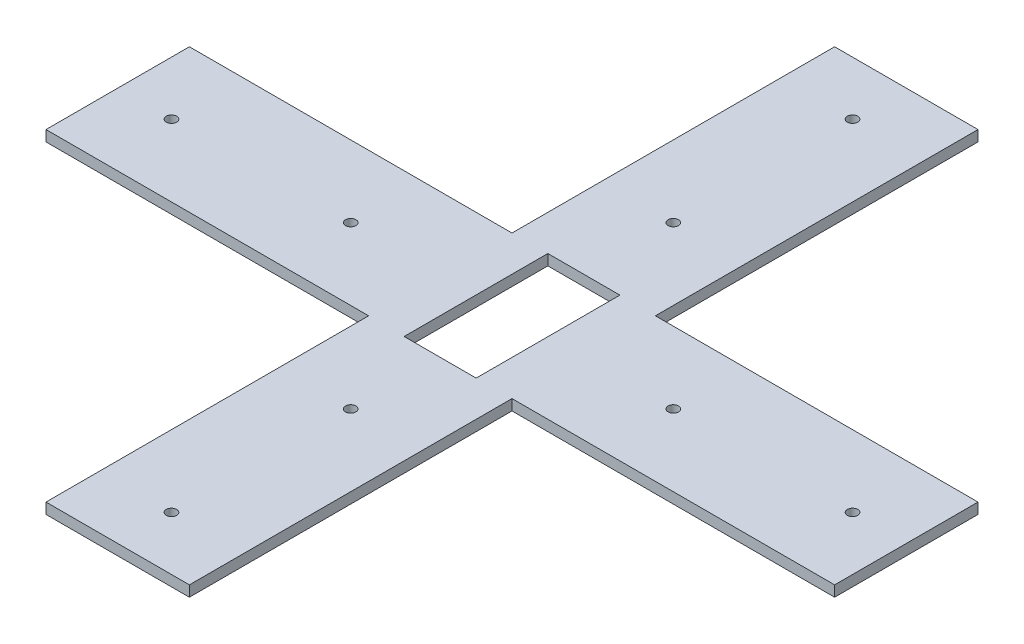
SolidWorks part; units mm, degrees
material "ABS"
ref_plane "Front Plane" through (0, 0, 0) normal (0, 0, 1) x (1, 0, 0)
ref_plane "Top Plane" through (0, 0, 0) normal (0, 1, 0) x (1, 0, 0)
ref_plane "Right Plane" through (0, 0, 0) normal (1, 0, 0) x (0, 0, -1)
sketch "Sketch1" plane through (0, 0, 0) normal (0, 1, 0) x (1, 0, 0)
  line L0 (-10.05, 20) -> (10.05, 20)
  line L1 (-10.05, 20.05) -> (10.05, 20.05)
  line L2 (-10.05, 20.05) -> (-10.05, -20.05)
  line L3 (-10.05, -20.05) -> (10.05, -20.05)
  line L4 (10.05, 20.05) -> (10.05, -20.05)
  line L5 (-10.05, 20.05) -> (10.05, -20.05) construction
  line L6 (-10.05, -20.05) -> (10.05, 20.05) construction
  line L7 (-20, 110) -> (20, 110)
  line L8 (-20, 110) -> (-20, 20)
  line L9 (-20, -110) -> (20, -110)
  line L10 (20, 110) -> (20, 20)
  line L11 (-4.01, 20.05) -> (4.01, -20.05) construction
  line L12 (-4.01, -20.05) -> (4.01, 20.05) construction
  line L13 (-110, 20) -> (-20, 20)
  line L14 (-110, 20) -> (-110, -20)
  line L15 (-110, -20) -> (-20, -20)
  line L16 (110, 20) -> (110, -20)
  line L17 (-10.05, 2.01) -> (10.05, -2.01) construction
  line L18 (-10.05, -2.01) -> (10.05, 2.01) construction
  line L19 (0, 0) -> (0, 16.1139)
  line L20 (-20, -20) -> (-20, -110)
  line L21 (-10.05, -20) -> (10.05, -20)
  line L22 (20, -20) -> (110, -20)
  line L23 (20, -20) -> (20, -110)
  line L24 (0, 0) -> (28.374, 0)
  line L25 (20, 20) -> (110, 20)
  circle A0 centre (45, 0) radius 1.45
  circle A1 centre (95, 0) radius 1.45
  circle A2 centre (-95, 0) radius 1.45
  circle A3 centre (-45, 0) radius 1.45
  circle A4 centre (0, 95) radius 1.45
  circle A5 centre (0, 45) radius 1.45
  circle A6 centre (0, -45) radius 1.45
  circle A7 centre (0, -95) radius 1.45
  point P0 (0, 0)
  point P6 (0, 0)
  point P11 (0, 0)
  point P16 (-110, 0)
  point P38 (110, 0)
  point P49 (0, 110)
  dimension "D9" = 2.9
  dimension "D12" = 2.9
  dimension "D14" = 25
  dimension "D1" = 20.1
  dimension "D2" = 40.1
  dimension "D3" = 40
  dimension "D4" = 220
  dimension "D5" = 40
  dimension "D6" = 220
  dimension "D7" = 110
  dimension "D8" = 110
  dimension "D10" = 15
  dimension "D11" = 25
  dimension "D13" = 15
extrude "Boss-Extrude1" add sketch "Sketch1" along normal blind 3 contours L25 L10 L7 L8 L13 L14 L15 L20 L9 L23 L22 L16 L1 L4 L3 L2
